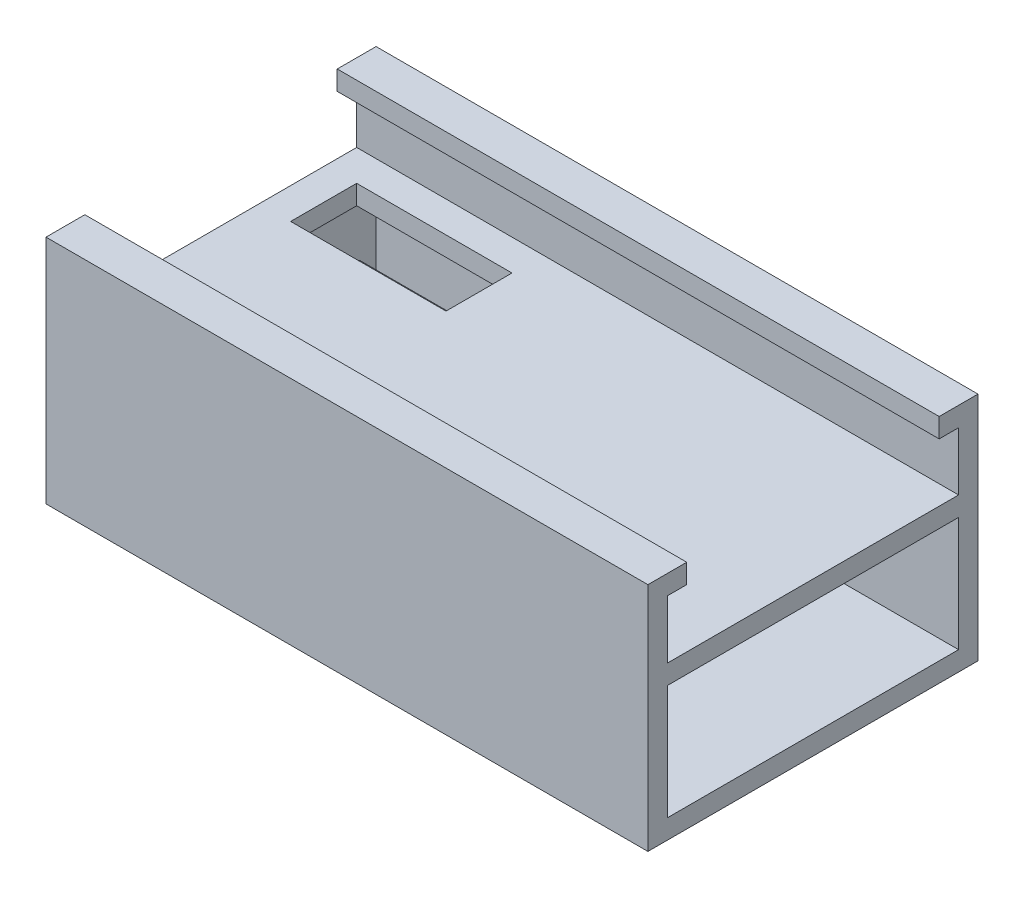
SolidWorks part; units mm, degrees
ref_plane "Front Plane" through (0, 0, 0) normal (0, 0, 1) x (1, 0, 0)
ref_plane "Top Plane" through (0, 0, 0) normal (0, 1, 0) x (1, 0, 0)
ref_plane "Right Plane" through (0, 0, 0) normal (1, 0, 0) x (0, 0, -1)
sketch "Sketch1" plane through (0, 0, 0) normal (0, 1, 0) x (1, 0, 0)
  line L0 (-4.3967, 14.7342) -> (-4.3967, 5.4342)
  line L1 (-28.9624, 14.7342) -> (126.0376, 14.7342)
  line L2 (-28.9624, 14.7342) -> (-28.9624, -70.2658)
  line L3 (-28.9624, -70.2658) -> (126.0376, -70.2658)
  line L4 (126.0376, 14.7342) -> (126.0376, -70.2658)
  line L5 (-15.1029, 5.4342) -> (44.4303, 5.4342)
  line L6 (-15.1029, 5.4342) -> (-15.1029, -15.9783)
  line L7 (-15.1029, -15.9783) -> (44.4303, -15.9783)
  line L8 (44.4303, 5.4342) -> (44.4303, -15.9783)
  dimension "D1" = 85
  dimension "D2" = 155
  dimension "D3" = 9.3
extrude "Boss-Extrude1" add sketch "Sketch1" along normal blind 5 contours L2 L1 L4 L3
sketch "Sketch2" plane through (0, 5, 0) normal (0, 1, 0) x (1, 0, 0)
  line L0 (-6.4452, 14.7342) -> (-6.4452, 5.4342)
  line L1 (-23.9624, 5.4342) -> (30.0376, 5.4342)
  line L2 (-23.9624, 5.4342) -> (-23.9624, -29.9658)
  line L3 (-23.9624, -29.9658) -> (30.0376, -29.9658)
  line L4 (30.0376, 5.4342) -> (30.0376, -29.9658)
  line L5 (-28.9624, 14.7342) -> (126.0376, 14.7342) construction
  line L6 (-28.9624, 0) -> (-23.9624, 0)
  line L7 (-28.9624, 14.7342) -> (-28.9624, -70.2658) construction
  line L9 (30.0376, 5.4342) -> (25.0376, 5.4342)
  line L10 (30.0376, 5.4342) -> (30.0376, -29.9658)
  line L11 (30.0376, -29.9658) -> (25.0376, -29.9658)
  line L12 (25.0376, 5.4342) -> (25.0376, -29.9658)
  line L14 (-23.9624, 5.4342) -> (25.0376, 5.4342)
  line L15 (-23.9624, 5.4342) -> (-23.9624, 0.4342)
  line L16 (-23.9624, 0.4342) -> (25.0376, 0.4342)
  line L17 (25.0376, 5.4342) -> (25.0376, 0.4342)
  dimension "D1" = 9.3
  dimension "D2" = 5
  dimension "D3" = 54
  dimension "D4" = 35.4
extrude "Boss-Extrude19" add sketch "Sketch2" along normal blind 5 contours L2 L1 L4 L3
sketch "Sketch14" plane through (0, 10, 0) normal (0, 1, 0) x (1, 0, 0)
  line L0 (-23.9624, -29.9658) -> (30.0376, -29.9658) construction
  line L1 (30.0376, 5.4342) -> (25.0376, 5.4342)
  line L2 (30.0376, 5.4342) -> (30.0376, -29.9658)
  line L3 (30.0376, -29.9658) -> (25.0376, -29.9658)
  line L4 (25.0376, 5.4342) -> (25.0376, -29.9658)
  dimension "D1" = 5
extrude "Boss-Extrude23" add sketch "Sketch14" along normal blind 9
sketch "Sketch17" plane through (0, 10, 0) normal (0, 1, 0) x (1, 0, 0)
  line L0 (25.0376, 5.4342) -> (25.0376, -29.9658) construction
  line L1 (-23.9624, 5.4342) -> (25.0376, 5.4342)
  line L2 (-23.9624, 5.4342) -> (-23.9624, 1.4342)
  line L3 (-23.9624, 1.4342) -> (25.0376, 1.4342)
  line L4 (25.0376, 5.4342) -> (25.0376, 1.4342)
  dimension "D1" = 4
extrude "Boss-Extrude24" add sketch "Sketch17" along normal blind 9 contours L2 L1 L4 L3
sketch "Sketch18" plane through (0, 0, -1.4342) normal (0, 0, 1) x (1, 0, 0)
  line L0 (25.0376, 19) -> (25.0376, 10) construction
  line L1 (-23.9624, 19) -> (25.0376, 19)
  line L2 (-23.9624, 19) -> (-23.9624, 14.5)
  line L3 (-23.9624, 14.5) -> (25.0376, 14.5)
  line L4 (25.0376, 19) -> (25.0376, 14.5)
  dimension "D1" = 4.5
extrude "Boss-Extrude25" add sketch "Sketch18" along normal blind 5 contours L2 L1 L4 L3
sketch "Sketch19" plane through (25.0376, 0, 0) normal (-1, 0, 0) x (0, 0, 1)
  line L1 (3.5658, 19) -> (20.9658, 19)
  line L2 (3.5658, 19) -> (3.5658, 14.5)
  line L3 (3.5658, 14.5) -> (20.9658, 14.5)
  line L4 (20.9658, 19) -> (20.9658, 14.5)
  dimension "D1" = 4.5
  dimension "D2" = 17.4
extrude "Boss-Extrude26" add sketch "Sketch19" along normal blind 5 contours L2 L1 L4 L3
sketch "Sketch20" plane through (0, 10, 0) normal (0, 1, 0) x (1, 0, 0)
  line L1 (25.0376, -29.9658) -> (-23.9624, -29.9658)
  line L2 (25.0376, -29.9658) -> (25.0376, -25.9658)
  line L3 (25.0376, -25.9658) -> (-23.9624, -25.9658)
  line L4 (-23.9624, -29.9658) -> (-23.9624, -25.9658)
  dimension "D1" = 4
extrude "Boss-Extrude27" add sketch "Sketch20" along normal blind 9
sketch "Sketch21" plane through (0, 0, 29.9658) normal (0, 0, 1) x (1, 0, 0)
  line L1 (-23.9624, 19) -> (25.0376, 19)
  line L2 (-23.9624, 19) -> (-23.9624, 14.5)
  line L3 (-23.9624, 14.5) -> (25.0376, 14.5)
  line L4 (25.0376, 19) -> (25.0376, 14.5)
  dimension "D1" = 49
  dimension "D2" = 4.5
extrude "Boss-Extrude28" add sketch "Sketch21" against normal blind 9 contours L2 L1 L4 L3
sketch "Sketch24" plane through (0, 19, 0) normal (0, 1, 0) x (1, 0, 0)
  line L0 (-23.9624, -3.5658) -> (20.0376, -3.5658) construction
  line L1 (-20.9624, 1.7342) -> (19.0376, 1.7342)
  line L2 (-20.9624, 1.7342) -> (-20.9624, -3.5658)
  line L3 (-20.9624, -3.5658) -> (19.0376, -3.5658)
  line L4 (19.0376, 1.7342) -> (19.0376, -3.5658)
  dimension "D2" = 40
  dimension "D3" = 5.3
extrude "Cut-Extrude3" cut sketch "Sketch24" against normal blind 9 contours L2 L1 L4 L3
sketch "Sketch26" plane through (0, 5, 0) normal (0, 1, 0) x (1, 0, 0)
  line L1 (126.0376, 14.7342) -> (-28.9624, 14.7342)
  line L2 (126.0376, 14.7342) -> (126.0376, 9.7342)
  line L3 (126.0376, 9.7342) -> (-28.9624, 9.7342)
  line L4 (-28.9624, 14.7342) -> (-28.9624, 9.7342)
  dimension "D1" = 155
  dimension "D2" = 5
extrude "Boss-Extrude29" add sketch "Sketch26" along normal blind 54.5 contours L2 L1 L4 L3
sketch "Sketch27" plane through (0, 0, -9.7342) normal (0, 0, 1) x (1, 0, 0)
  line L0 (-28.9624, 59.5) -> (-28.9624, 5) construction
  line L1 (-28.9624, 39.5) -> (126.0376, 39.5)
  line L2 (-28.9624, 39.5) -> (-28.9624, 34.5)
  line L3 (-28.9624, 34.5) -> (126.0376, 34.5)
  line L4 (126.0376, 39.5) -> (126.0376, 34.5)
  line L5 (126.0376, 59.5) -> (126.0376, 5) construction
  dimension "D2" = 5
extrude "Boss-Extrude30" add sketch "Sketch27" along normal blind 75 contours L2 L1 L4 L3
sketch "Sketch28" plane through (0, 5, 0) normal (0, 1, 0) x (1, 0, 0)
  line L1 (126.0376, -70.2658) -> (-28.9624, -70.2658)
  line L2 (126.0376, -70.2658) -> (126.0376, -65.2658)
  line L3 (126.0376, -65.2658) -> (-28.9624, -65.2658)
  line L4 (-28.9624, -70.2658) -> (-28.9624, -65.2658)
extrude "Boss-Extrude31" add sketch "Sketch28" along normal blind 54.5
sketch "Sketch29" plane through (-28.9624, 0, 0) normal (-1, 0, 0) x (0, 0, 1)
  line L1 (-9.7342, 39.5) -> (65.2658, 39.5)
  line L2 (-9.7342, 39.5) -> (-9.7342, 5)
  line L3 (-9.7342, 5) -> (65.2658, 5)
  line L4 (65.2658, 39.5) -> (65.2658, 5)
extrude "Boss-Extrude32" add sketch "Sketch29" against normal blind 5 contours L2 L1 L4 L3
sketch "Sketch30" plane through (0, 39.5, 0) normal (0, 1, 0) x (1, 0, 0)
  line L1 (-20.9624, 1.7342) -> (19.0376, 1.7342)
  line L2 (-20.9624, 1.7342) -> (-20.9624, -15.2658)
  line L3 (-20.9624, -15.2658) -> (19.0376, -15.2658)
  line L4 (19.0376, 1.7342) -> (19.0376, -15.2658)
  dimension "D3" = 17
  dimension "D4" = 40
extrude "Cut-Extrude4" cut sketch "Sketch30" against normal blind 5 contours L2 L1 L4 L3
sketch "Sketch31" plane through (-28.9624, 0, 0) normal (-1, 0, 0) x (0, 0, 1)
  line L1 (-1.4342, 10) -> (25.9658, 10)
  line L2 (-1.4342, 10) -> (-1.4342, 14.5)
  line L3 (-1.4342, 14.5) -> (25.9658, 14.5)
  line L4 (25.9658, 10) -> (25.9658, 14.5)
  dimension "D3" = 4.5
  dimension "D4" = 27.4
extrude "Cut-Extrude6" cut sketch "Sketch31" against normal blind 5 contours L2 L1 L4 L3
sketch "Sketch32" plane through (0, 0, 70.2658) normal (0, 0, 1) x (1, 0, 0)
  line L0 (126.0376, 59.5) -> (126.0376, 0) construction
  line L1 (-28.9624, 59.5) -> (126.0376, 59.5)
  line L2 (-28.9624, 59.5) -> (-28.9624, 54.5)
  line L3 (-28.9624, 54.5) -> (126.0376, 54.5)
  line L4 (126.0376, 59.5) -> (126.0376, 54.5)
  dimension "D1" = 5
extrude "Boss-Extrude33" add sketch "Sketch32" against normal blind 10 contours L2 L1 L4 L3
sketch "Sketch33" plane through (0, 0, -14.7342) normal (0, 0, -1) x (-1, 0, 0)
  line L0 (28.9624, 59.5) -> (28.9624, 0) construction
  line L1 (-126.0376, 59.5) -> (28.9624, 59.5)
  line L2 (-126.0376, 59.5) -> (-126.0376, 54.5)
  line L3 (-126.0376, 54.5) -> (28.9624, 54.5)
  line L4 (28.9624, 59.5) -> (28.9624, 54.5)
  dimension "D1" = 5
extrude "Boss-Extrude34" add sketch "Sketch33" against normal blind 10 contours L2 L1 L4 L3
